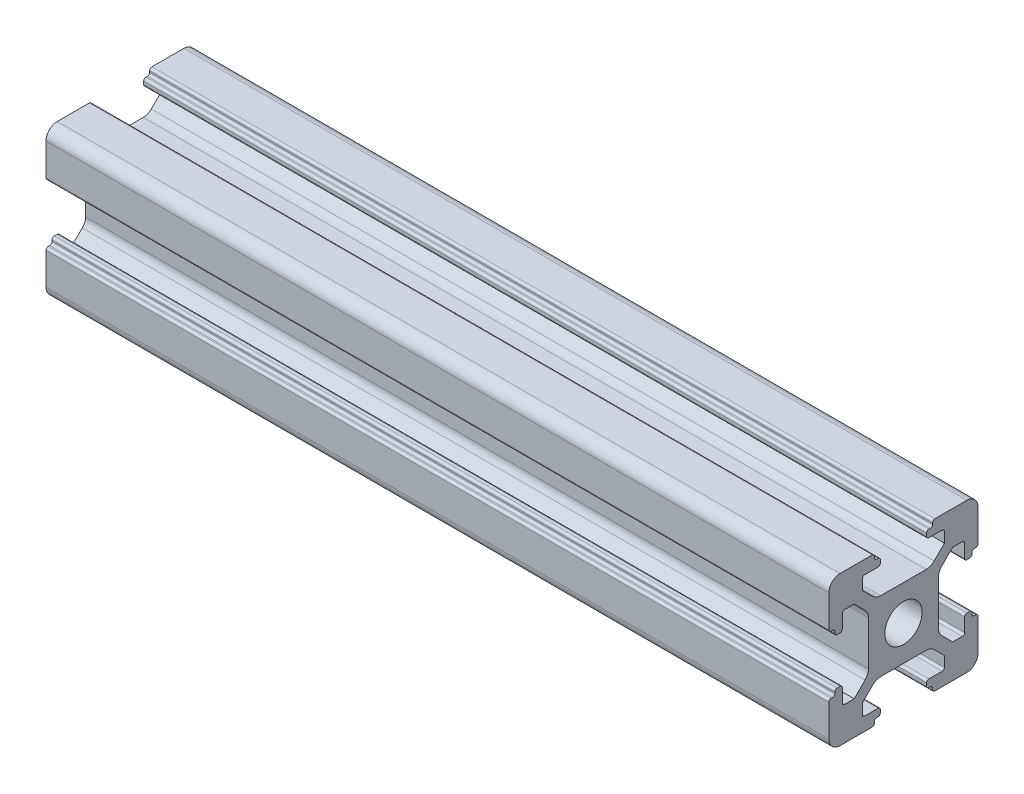
SolidWorks part; units mm, degrees
ref_plane "Front Plane" through (0, 0, 0) normal (0, 0, 1) x (1, 0, 0)
ref_plane "Top Plane" through (0, 0, 0) normal (0, 1, 0) x (1, 0, 0)
ref_plane "Right Plane" through (0, 0, 0) normal (1, 0, 0) x (0, 0, -1)
sketch "Sketch1" plane through (0, 0, 0) normal (1, 0, 0) x (0, 0, -1)
  line L0 (0, 0) -> (0, 50000) construction
  line L1 (0, 0) -> (-50000, 0) construction
  line L2 (10, 4.2) -> (10, 8.5)
  line L3 (9.7, 3.9) -> (9.5, 3.9)
  line L4 (9.2, 3.6) -> (9.2, 3.4)
  line L5 (8.9, 3.1) -> (8.5, 3.1)
  line L6 (8.2, 3.4) -> (8.2, 5.2)
  line L7 (7.9, 5.5) -> (6.6, 5.5)
  line L8 (6.6, 5.5) -> (5.1393, 4.0393)
  line L9 (8.5, 10) -> (4.2, 10)
  line L10 (3.9, 9.7) -> (3.9, 9.5)
  line L11 (3.6, 9.2) -> (3.4, 9.2)
  line L12 (3.1, 8.9) -> (3.1, 8.5)
  line L13 (3.4, 8.2) -> (5.2, 8.2)
  line L14 (5.5, 7.9) -> (5.5, 6.5213)
  line L15 (5.5, 6.5213) -> (4.118, 5.1393)
  line L16 (4.7, 2.9787) -> (4.7, -2.9787)
  line L17 (3.0574, 4.7) -> (-3.0574, 4.7)
  line L18 (-4.7, 2.9787) -> (-4.7, -2.9787)
  line L19 (-5.5, 6.5213) -> (-4.118, 5.1393)
  line L20 (-5.5, 7.9) -> (-5.5, 6.5213)
  line L21 (-3.4, 8.2) -> (-5.2, 8.2)
  line L22 (-3.1, 8.9) -> (-3.1, 8.5)
  line L23 (-3.6, 9.2) -> (-3.4, 9.2)
  line L24 (-3.9, 9.7) -> (-3.9, 9.5)
  line L25 (-8.5, 10) -> (-4.2, 10)
  line L26 (-6.6, 5.5) -> (-5.1393, 4.0393)
  line L27 (-7.9, 5.5) -> (-6.6, 5.5)
  line L28 (-8.2, 3.4) -> (-8.2, 5.2)
  line L29 (-8.9, 3.1) -> (-8.5, 3.1)
  line L30 (-9.2, 3.6) -> (-9.2, 3.4)
  line L31 (-9.7, 3.9) -> (-9.5, 3.9)
  line L32 (-10, 4.2) -> (-10, 8.5)
  line L33 (-10, -4.2) -> (-10, -8.5)
  line L34 (-9.7, -3.9) -> (-9.5, -3.9)
  line L35 (-9.2, -3.6) -> (-9.2, -3.4)
  line L36 (-8.9, -3.1) -> (-8.5, -3.1)
  line L37 (-8.2, -3.4) -> (-8.2, -5.2)
  line L38 (-7.9, -5.5) -> (-6.6, -5.5)
  line L39 (-6.6, -5.5) -> (-5.1393, -4.0393)
  line L40 (-8.5, -10) -> (-4.2, -10)
  line L41 (-3.9, -9.7) -> (-3.9, -9.5)
  line L42 (-3.6, -9.2) -> (-3.4, -9.2)
  line L43 (-3.1, -8.9) -> (-3.1, -8.5)
  line L44 (-3.4, -8.2) -> (-5.2, -8.2)
  line L45 (-5.5, -7.9) -> (-5.5, -6.5213)
  line L46 (-5.5, -6.5213) -> (-4.118, -5.1393)
  line L47 (3.0574, -4.7) -> (-3.0574, -4.7)
  line L48 (5.5, -6.5213) -> (4.118, -5.1393)
  line L49 (5.5, -7.9) -> (5.5, -6.5213)
  line L50 (3.4, -8.2) -> (5.2, -8.2)
  line L51 (3.1, -8.9) -> (3.1, -8.5)
  line L52 (3.6, -9.2) -> (3.4, -9.2)
  line L53 (3.9, -9.7) -> (3.9, -9.5)
  line L54 (8.5, -10) -> (4.2, -10)
  line L55 (6.6, -5.5) -> (5.1393, -4.0393)
  line L56 (7.9, -5.5) -> (6.6, -5.5)
  line L57 (8.2, -3.4) -> (8.2, -5.2)
  line L58 (8.9, -3.1) -> (8.5, -3.1)
  line L59 (9.2, -3.6) -> (9.2, -3.4)
  line L60 (9.7, -3.9) -> (9.5, -3.9)
  line L61 (10, -4.2) -> (10, -8.5)
  circle A0 centre (0, 0) radius 2.5
  arc A1 (10, 8.5) -> (8.5, 10) centre (8.5, 8.5) ccw
  arc A2 (9.7, 3.9) -> (10, 4.2) centre (9.7, 4.2) ccw
  arc A3 (9.5, 3.9) -> (9.2, 3.6) centre (9.5, 3.6) ccw
  arc A4 (9.2, 3.4) -> (8.9, 3.1) centre (8.9, 3.4) cw
  arc A5 (8.5, 3.1) -> (8.2, 3.4) centre (8.5, 3.4) cw
  arc A6 (8.2, 5.2) -> (7.9, 5.5) centre (7.9, 5.2) ccw
  arc A7 (5.2, 8.2) -> (5.5, 7.9) centre (5.2, 7.9) cw
  arc A8 (3.1, 8.5) -> (3.4, 8.2) centre (3.4, 8.5) ccw
  arc A9 (3.4, 9.2) -> (3.1, 8.9) centre (3.4, 8.9) ccw
  arc A10 (4.2, 10) -> (3.9, 9.7) centre (4.2, 9.7) ccw
  arc A11 (3.9, 9.5) -> (3.6, 9.2) centre (3.6, 9.5) cw
  arc A12 (4.7, 2.9787) -> (5.1393, 4.0393) centre (6.2, 2.9787) cw
  arc A13 (3.0574, 4.7) -> (4.118, 5.1393) centre (3.0574, 6.2) ccw
  arc A14 (-3.0574, 4.7) -> (-4.118, 5.1393) centre (-3.0574, 6.2) cw
  arc A15 (-4.7, 2.9787) -> (-5.1393, 4.0393) centre (-6.2, 2.9787) ccw
  arc A16 (-3.9, 9.5) -> (-3.6, 9.2) centre (-3.6, 9.5) ccw
  arc A17 (-4.2, 10) -> (-3.9, 9.7) centre (-4.2, 9.7) cw
  arc A18 (-3.4, 9.2) -> (-3.1, 8.9) centre (-3.4, 8.9) cw
  arc A19 (-3.1, 8.5) -> (-3.4, 8.2) centre (-3.4, 8.5) cw
  arc A20 (-5.2, 8.2) -> (-5.5, 7.9) centre (-5.2, 7.9) ccw
  arc A21 (-8.2, 5.2) -> (-7.9, 5.5) centre (-7.9, 5.2) cw
  arc A22 (-8.5, 3.1) -> (-8.2, 3.4) centre (-8.5, 3.4) ccw
  arc A23 (-9.2, 3.4) -> (-8.9, 3.1) centre (-8.9, 3.4) ccw
  arc A24 (-9.5, 3.9) -> (-9.2, 3.6) centre (-9.5, 3.6) cw
  arc A25 (-9.7, 3.9) -> (-10, 4.2) centre (-9.7, 4.2) cw
  arc A26 (-10, 8.5) -> (-8.5, 10) centre (-8.5, 8.5) cw
  arc A27 (-10, -8.5) -> (-8.5, -10) centre (-8.5, -8.5) ccw
  arc A28 (-9.7, -3.9) -> (-10, -4.2) centre (-9.7, -4.2) ccw
  arc A29 (-9.5, -3.9) -> (-9.2, -3.6) centre (-9.5, -3.6) ccw
  arc A30 (-9.2, -3.4) -> (-8.9, -3.1) centre (-8.9, -3.4) cw
  arc A31 (-8.5, -3.1) -> (-8.2, -3.4) centre (-8.5, -3.4) cw
  arc A32 (-8.2, -5.2) -> (-7.9, -5.5) centre (-7.9, -5.2) ccw
  arc A33 (-5.2, -8.2) -> (-5.5, -7.9) centre (-5.2, -7.9) cw
  arc A34 (-3.1, -8.5) -> (-3.4, -8.2) centre (-3.4, -8.5) ccw
  arc A35 (-3.4, -9.2) -> (-3.1, -8.9) centre (-3.4, -8.9) ccw
  arc A36 (-4.2, -10) -> (-3.9, -9.7) centre (-4.2, -9.7) ccw
  arc A37 (-3.9, -9.5) -> (-3.6, -9.2) centre (-3.6, -9.5) cw
  arc A38 (-4.7, -2.9787) -> (-5.1393, -4.0393) centre (-6.2, -2.9787) cw
  arc A39 (-3.0574, -4.7) -> (-4.118, -5.1393) centre (-3.0574, -6.2) ccw
  arc A40 (3.0574, -4.7) -> (4.118, -5.1393) centre (3.0574, -6.2) cw
  arc A41 (4.7, -2.9787) -> (5.1393, -4.0393) centre (6.2, -2.9787) ccw
  arc A42 (3.9, -9.5) -> (3.6, -9.2) centre (3.6, -9.5) ccw
  arc A43 (4.2, -10) -> (3.9, -9.7) centre (4.2, -9.7) cw
  arc A44 (3.4, -9.2) -> (3.1, -8.9) centre (3.4, -8.9) cw
  arc A45 (3.1, -8.5) -> (3.4, -8.2) centre (3.4, -8.5) cw
  arc A46 (5.2, -8.2) -> (5.5, -7.9) centre (5.2, -7.9) ccw
  arc A47 (8.2, -5.2) -> (7.9, -5.5) centre (7.9, -5.2) cw
  arc A48 (8.5, -3.1) -> (8.2, -3.4) centre (8.5, -3.4) ccw
  arc A49 (9.2, -3.4) -> (8.9, -3.1) centre (8.9, -3.4) ccw
  arc A50 (9.5, -3.9) -> (9.2, -3.6) centre (9.5, -3.6) cw
  arc A51 (9.7, -3.9) -> (10, -4.2) centre (9.7, -4.2) cw
  arc A52 (10, -8.5) -> (8.5, -10) centre (8.5, -8.5) cw
  point P24 (10, 10)
  point P41 (3.1, 9.2)
  point P44 (3.9, 10)
  point P94 (4.7, 0)
  point P95 (0, 4.7)
  point P175 (0, -4.7)
  point P176 (-4.7, 0)
  dimension "D1" = 5
  dimension "D15" = 1.5
  dimension "D16" = 0.3
  dimension "D19" = 1.5
  dimension "D2" = 20
  dimension "D3" = 1.8
  dimension "D4" = 6.2
  dimension "D5" = 3.4
  dimension "D6" = 11
  dimension "D7" = 6.1
  dimension "D8" = 1.5
  dimension "D9" = 20
  dimension "D10" = 6.1
  dimension "D11" = 6.2
  dimension "D12" = 11
  dimension "D13" = 45
  dimension "D14" = 1.8
  dimension "D17" = 3.5
  dimension "D18" = 3.5
extrude "Boss-Extrude2" add sketch "Sketch1" along normal mid plane 105
